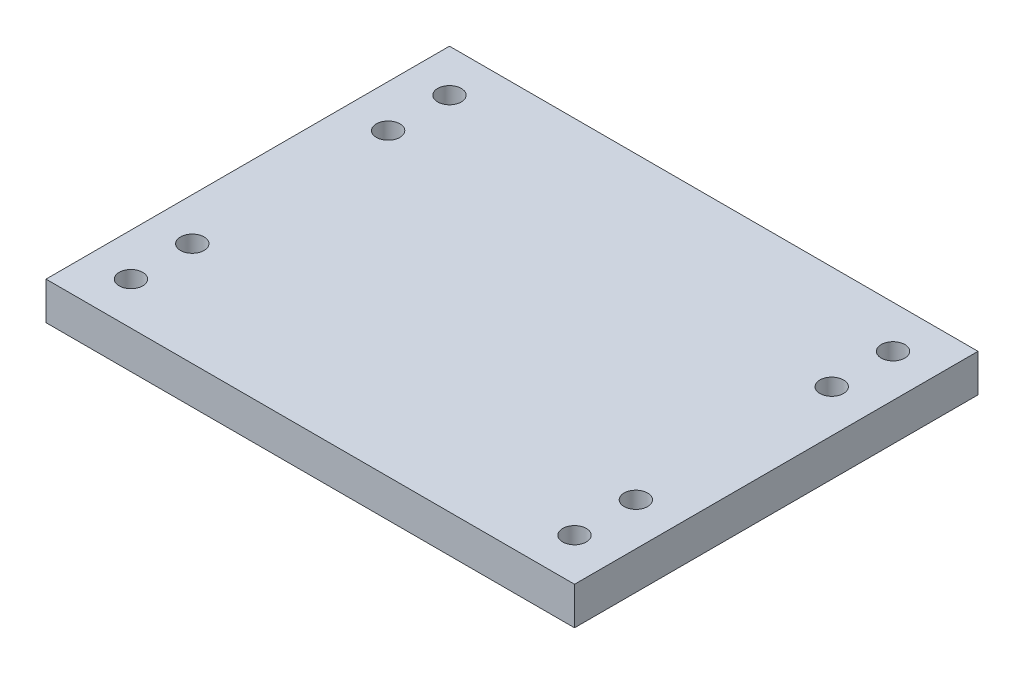
SolidWorks part; units mm, degrees
ref_plane "Front Plane" through (0, 0, 0) normal (0, 0, 1) x (1, 0, 0)
ref_plane "Top Plane" through (0, 0, 0) normal (0, 1, 0) x (1, 0, 0)
ref_plane "Right Plane" through (0, 0, 0) normal (1, 0, 0) x (0, 0, -1)
sketch "Sketch1" plane through (0, 0, 0) normal (0, 1, 0) x (1, 0, 0)
  line L1 (-11.2, 8.55) -> (11.2, 8.55)
  line L2 (-11.2, 8.55) -> (-11.2, -8.55)
  line L3 (-11.2, -8.55) -> (11.2, -8.55)
  line L4 (11.2, 8.55) -> (11.2, -8.55)
  line L5 (-11.2, 8.55) -> (11.2, -8.55) construction
  line L6 (-11.2, -8.55) -> (11.2, 8.55) construction
  point P0 (0, 0)
  dimension "D1" = 17.1
  dimension "D2" = 22.4
extrude "MAIN BODY" add sketch "Sketch1" along normal blind 1.6
sketch "Sketch2" plane through (0, 1.6, 0) normal (0, 1, 0) x (1, 0, 0)
  line L0 (-9.4, 6.75) -> (-9.4, 4.15) construction
  line L1 (11.2, 8.55) -> (-11.2, 8.55) construction
  line L2 (-11.2, 8.55) -> (-11.2, -8.55) construction
  circle A0 centre (-9.4, 6.75) radius 0.5
  circle A1 centre (-9.4, 4.15) radius 0.5
  dimension "D1" = 1
  dimension "Width" = 2.6
  dimension "XDim" = 1.8
  dimension "YDim" = 1.8
extrude "SOLDERED CONNECTION HOLES" cut sketch "Sketch2" against normal through all
mirror "Mirror1" about plane through (0, 0, 0) normal (1, 0, 0) of "SOLDERED CONNECTION HOLES"
mirror "Mirror2" about plane through (0, 0, 0) normal (0, 0, 1) of "SOLDERED CONNECTION HOLES", "Mirror1"
